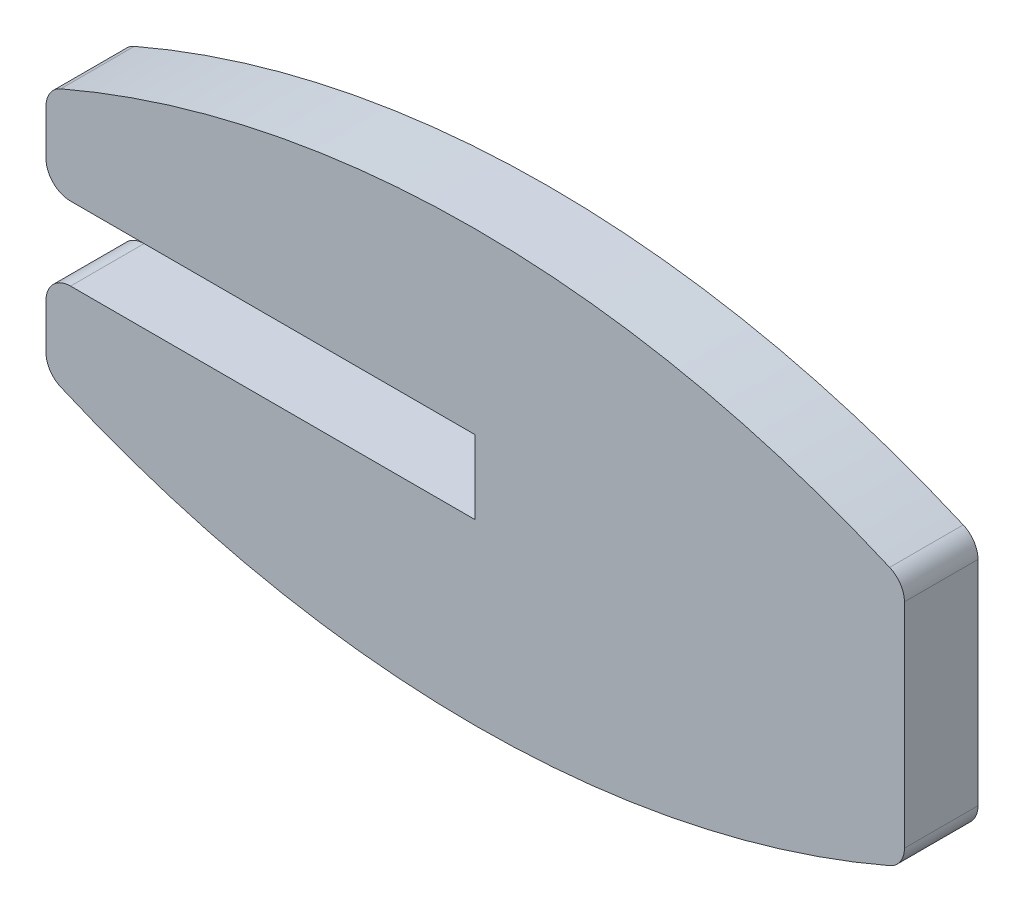
SolidWorks part; units mm, degrees
ref_plane "Спереди" through (0, 0, 0) normal (0, 0, 1) x (1, 0, 0)
ref_plane "Сверху" through (0, 0, 0) normal (0, 1, 0) x (1, 0, 0)
ref_plane "Справа" through (0, 0, 0) normal (1, 0, 0) x (0, 0, -1)
sketch "Эскиз1" plane through (0, 0, 0) normal (0, 0, 1) x (1, 0, 0)
  line L0 (55, 0) -> (-55, 0) construction
  line L1 (-17.5, -5) -> (17.5, -5)
  line L2 (-17.5, -5) -> (-17.5, 5)
  line L3 (-17.5, 5) -> (17.5, 5)
  line L4 (17.5, -5) -> (17.5, 5)
  line L5 (-17.5, -5) -> (17.5, 5) construction
  line L6 (-17.5, 5) -> (17.5, -5) construction
  line L7 (0, 1.5) -> (-17.5, 1.5)
  line L8 (0, 1.5) -> (0, -1.5)
  line L9 (0, -1.5) -> (-17.5, -1.5)
  line L10 (-17.5, 1.5) -> (-17.5, -1.5)
  arc A0 (-17.5, 5) -> (17.5, 5) centre (0, -33.7298) cw
  arc A1 (-17.5, -5) -> (17.5, -5) centre (0, 33.7298) ccw
  point P0 (0, 0)
  point P10 (0, 0)
  dimension "D4" = 42.5
  dimension "D1" = 35
  dimension "D2" = 10
  dimension "D3" = 3
extrude "Бобышка-Вытянуть1" add sketch "Эскиз1" along normal blind 3 contours L8 L9 L2 L1 L4 L3 L7 | A0 L3 | L1 A1
fillet "Скругление1" radius 1 6 edges at (17.5, -5, 1.5) (17.5, 5, 1.5) (-17.5, 5, 1.5) (-17.5, -5, 1.5) (-17.5, -1.5, 1.5) (-17.5, 1.5, 1.5)
